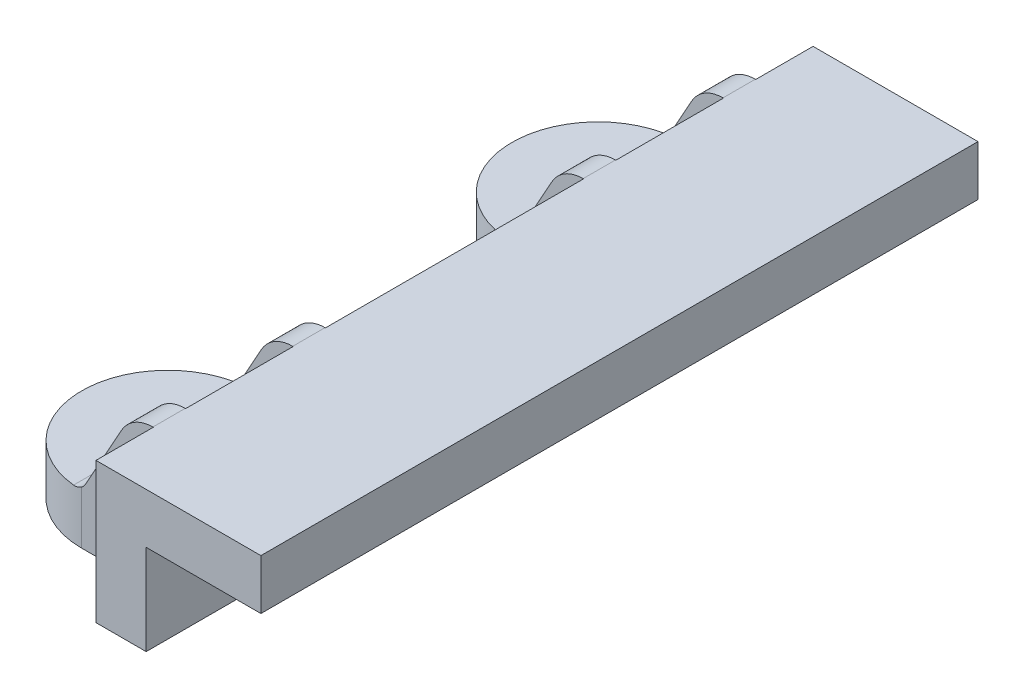
SolidWorks part; units mm, degrees
material "Acrílico (Impacto medio-alto)"
ref_plane "Alzado" through (0, 0, 0) normal (0, 0, 1) x (1, 0, 0)
ref_plane "Planta" through (0, 0, 0) normal (0, 1, 0) x (1, 0, 0)
ref_plane "Vista lateral" through (0, 0, 0) normal (1, 0, 0) x (0, 0, -1)
sketch "Croquis1" plane through (0, 0, 0) normal (0, 0, 1) x (1, 0, 0)
  line L0 (0, 0) -> (0, 9.8)
  line L1 (0, 9.8) -> (11.5, 9.8)
  line L2 (11.5, 9.8) -> (11.5, 6.3)
  line L3 (11.5, 6.3) -> (3.5, 6.3)
  line L4 (3.5, 6.3) -> (3.5, 0)
  line L5 (3.5, 0) -> (0, 0)
  dimension "D1" = 3.5
  dimension "D2" = 8
  dimension "D3" = 3.5
  dimension "D4" = 6.3
extrude "Saliente-Extruir1" add sketch "Croquis1" along normal mid plane 50
sketch "Croquis2" plane through (0, 0, 0) normal (0, 1, 0) x (1, 0, 0)
  line L0 (0, -25) -> (0, 25) construction
  line L1 (0, 9) -> (-5, 9)
  line L2 (0, 9) -> (0, 21)
  line L3 (0, 21) -> (-5, 21)
  line L5 (11.5, 25) -> (0, 25) construction
  arc A0 (-5, 21) -> (-5, 9) centre (-5, 15) ccw
  circle A1 centre (-5, 15) radius 2.25
  point P6 (0, 15)
  dimension "D4" = 4.5
  dimension "D1" = 10
  dimension "D2" = 12
  dimension "D3" = 5
extrude "Saliente-Extruir2" add sketch "Croquis2" along normal blind 3.5
sketch "Croquis3" plane through (0, 0, -9) normal (0, 0, 1) x (1, 0, 0)
  line L1 (0, 9.8) -> (0, 3.5)
  line L2 (0, 9.8) -> (0, 0) construction
  line L3 (-5, 3.5) -> (0, 3.5) construction
  line L4 (0, 3.5) -> (-5, 3.5)
  line L5 (-5, 3.5) -> (-1.5, 9.8)
  line L6 (-1.5, 9.8) -> (0, 9.8)
  dimension "D1" = 1.5
extrude "Saliente-Extruir3" add sketch "Croquis3" against normal blind 2.25
fillet "Redondeo3" radius 1 1 edges at (-5, 3.5, -10.125)
fillet "Redondeo5" radius 2.5 1 edges at (-1.5, 9.8, -10.125)
ref_plane "Plano1" through (0, 0, -15) normal (0, 0, -1) x (-1, 0, 0)
mirror "Simetría1" about plane through (0, 0, -15) normal (0, 0, -1) of "Saliente-Extruir3", "Redondeo3", "Redondeo5"
mirror "Simetría4" about plane through (0, 0, 0) normal (0, 0, 1) of "Saliente-Extruir2", "Saliente-Extruir3", "Redondeo3", "Redondeo5"
ref_plane "Plano2" through (0, 0, 15) normal (0, 0, -1) x (-1, 0, 0)
sketch "Croquis4" plane through (0, 0, 21) normal (0, 0, 1) x (1, 0, 0)
  line L0 (0, 3.5) -> (-5, 3.5)
  line L1 (-5, 3.5) -> (-1.5, 9.8)
  line L2 (0, 9.8) -> (-1.5, 9.8)
  line L4 (0, 3.5) -> (0, 9.8)
  dimension "D1" = 1.5
extrude "Saliente-Extruir4" add sketch "Croquis4" against normal blind 2.25
fillet "Redondeo6" radius 2.5 1 edges at (-1.5, 9.8, 19.875)
fillet "Redondeo7" radius 1 1 edges at (-5, 3.5, 19.875)
